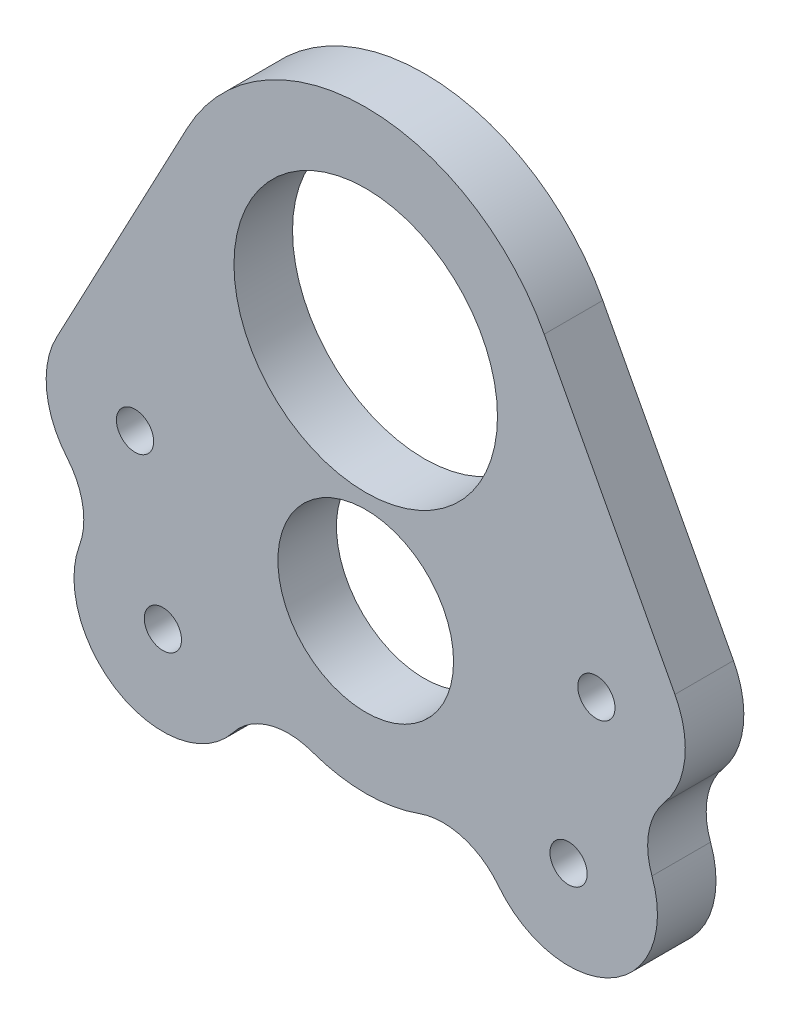
SolidWorks part; units mm, degrees
ref_plane "Front Plane" through (0, 0, 0) normal (0, 0, 1) x (1, 0, 0)
ref_plane "Top Plane" through (0, 0, 0) normal (0, 1, 0) x (1, 0, 0)
ref_plane "Right Plane" through (0, 0, 0) normal (1, 0, 0) x (0, 0, -1)
sketch "Sketch1" plane through (0, 0, 0) normal (0, 0, 1) x (1, 0, 0)
  line L0 (0, 0) -> (0, 25.4) construction
  line L1 (-33.5305, 8.9259) -> (-19.3554, 35.662)
  line L2 (33.5305, 8.9259) -> (19.3554, 35.662)
  circle A0 centre (0, 0) radius 25.4 construction
  circle A1 centre (0, 25.4) radius 2.0193 construction
  circle A2 centre (16.3268, 19.4575) radius 2.0193 construction
  circle A3 centre (25.0141, 4.4107) radius 2.0193
  circle A4 centre (21.997, -12.7) radius 2.0193
  circle A5 centre (8.6873, -23.8682) radius 2.0193 [skipped]
  circle A6 centre (-8.6873, -23.8682) radius 2.0193 [skipped]
  circle A7 centre (-21.997, -12.7) radius 2.0193
  circle A8 centre (-25.0141, 4.4107) radius 2.0193
  circle A9 centre (-16.3268, 19.4575) radius 2.0193 construction
  circle A10 centre (0, 25.4) radius 14.2875
  circle A11 centre (0, 0) radius 9.525
  arc A12 (19.3554, 35.662) -> (-19.3554, 35.662) centre (0, 25.4) ccw
  arc A13 (32.3743, -1.8138) -> (31.0422, -9.3682) centre (38.1926, -6.7344) ccw
  arc A14 (14.3917, -18.6224) -> (5.8013, -16.1337) centre (8.3796, -23.3042) ccw
  arc A15 (14.3917, -18.6224) -> (31.0422, -9.3682) centre (21.997, -12.7) ccw
  arc A16 (32.3743, -1.8138) -> (33.5305, 8.9259) centre (25.0141, 4.4107) ccw
  arc A17 (-31.0422, -9.3682) -> (-32.3743, -1.8138) centre (-38.1926, -6.7344) ccw
  arc A18 (-14.3917, -18.6224) -> (-5.8013, -16.1337) centre (-8.3796, -23.3042) cw
  arc A19 (-5.8013, -16.1337) -> (5.8013, -16.1337) centre (0, 0) ccw
  arc A20 (-33.5305, 8.9259) -> (-32.3743, -1.8138) centre (-25.0141, 4.4107) ccw
  arc A25 (-31.0422, -9.3682) -> (-14.3917, -18.6224) centre (-21.997, -12.7) ccw
  point P24 (0, 0)
  dimension "D1" = 50.8
  dimension "D2" = 4.0386
  dimension "D4" = 4.0386
  dimension "D5" = 28.575
  dimension "D6" = 19.05
  dimension "D7" = 7.62
  dimension "D8" = 7.62
  dimension "D9" = 7.62
  dimension "D3" = 9
extrude "Boss-Extrude1" add sketch "Sketch1" along normal blind 6.35
